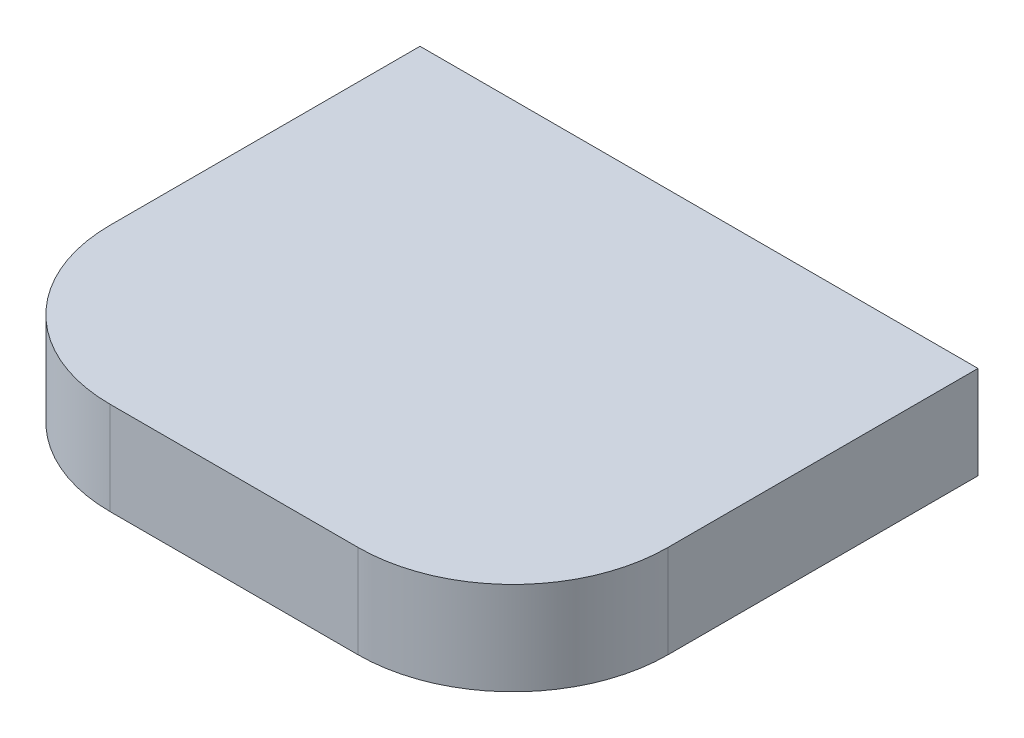
SolidWorks part; units mm, degrees
ref_plane "Front Plane" through (0, 0, 0) normal (0, 0, 1) x (1, 0, 0)
ref_plane "Top Plane" through (0, 0, 0) normal (0, 1, 0) x (1, 0, 0)
ref_plane "Right Plane" through (0, 0, 0) normal (1, 0, 0) x (0, 0, -1)
sketch "Sketch1" plane through (0, 0, 0) normal (0, 1, 0) x (1, 0, 0)
  line L0 (22.86, 19.19) -> (-22.86, 19.19)
  line L1 (-22.86, 19.19) -> (-22.86, -6.21)
  line L2 (22.86, 19.19) -> (22.86, -6.21)
  line L3 (-10.16, -18.91) -> (10.16, -18.91)
  arc A0 (-22.86, -6.21) -> (-10.16, -18.91) centre (-10.16, -6.21) ccw
  arc A1 (22.86, -6.21) -> (10.16, -18.91) centre (10.16, -6.21) cw
  point P3 (0, 19.19)
  dimension "D3" = 12.7
  dimension "D5" = 12.7
  dimension "D1" = 45.72
  dimension "D2" = 25.4
  dimension "D4" = 25.4
  dimension "D6" = 22.86
extrude "Boss-Extrude1" add sketch "Sketch1" along normal blind 7.62
